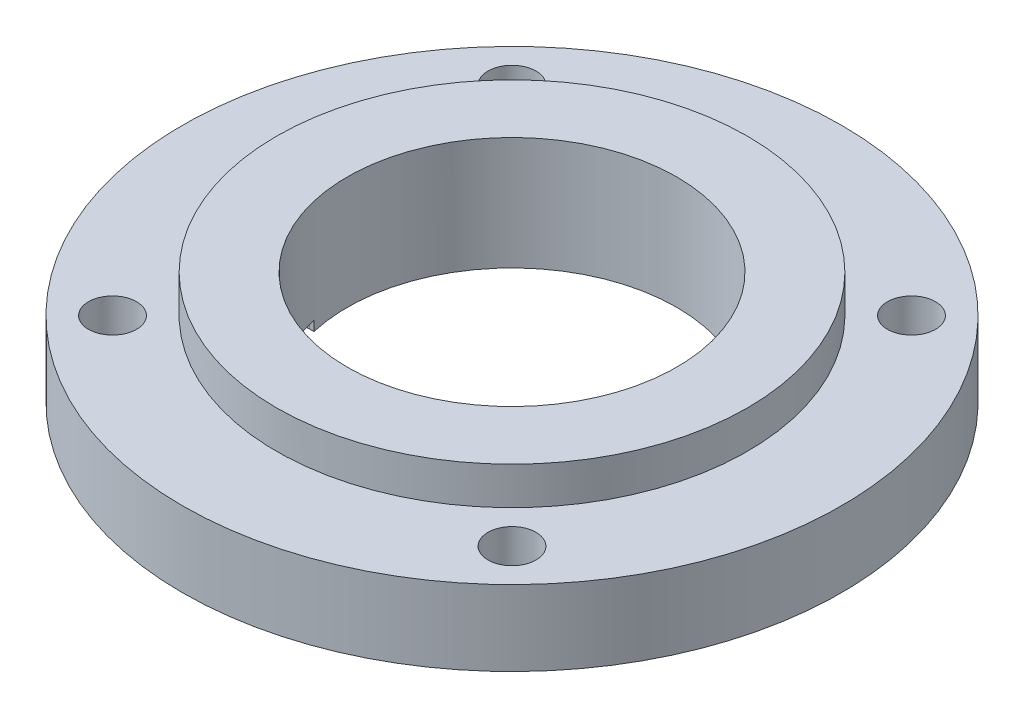
SolidWorks part; units mm, degrees
ref_plane "Front Plane" through (0, 0, 0) normal (0, 0, 1) x (1, 0, 0)
ref_plane "Top Plane" through (0, 0, 0) normal (0, 1, 0) x (1, 0, 0)
ref_plane "Right Plane" through (0, 0, 0) normal (1, 0, 0) x (0, 0, -1)
sketch "Sketch1" plane through (0, 0, 0) normal (0, 1, 0) x (1, 0, 0)
  circle A0 centre (0, 0) radius 25
  circle A1 centre (0, 0) radius 17.5
  dimension "D1" = 50
  dimension "D2" = 35
extrude "Boss-Extrude2" add sketch "Sketch1" along normal blind 12
sketch "Sketch4" plane through (0, 0, 0) normal (0, -1, 0) x (1, 0, 0)
  line L0 (0, 0) -> (0, 12.6931) construction
  line L1 (0, 0) -> (47.3741, 0) construction
  line L2 (0, 0) -> (-39.6318, 39.6318) construction
  circle A0 centre (0, 0) radius 35
  circle A1 centre (0, 0) radius 25
  circle A2 centre (-21.2132, 21.2132) radius 2.55
  circle A3 centre (21.2132, 21.2132) radius 2.55
  circle A4 centre (21.2132, -21.2132) radius 2.55
  circle A5 centre (-21.2132, -21.2132) radius 2.55
  point P19 (0, 0)
  point P22 (0, 0)
  dimension "D1" = 70
  dimension "D2" = 5.1
  dimension "D3" = 30
  dimension "D4" = 4
extrude "Boss-Extrude3" add sketch "Sketch4" against normal blind 8
sketch "Sketch2" plane through (0, 0, 0) normal (0, 1, 0) x (1, 0, 0)
  line L0 (-7.8, -11.4396) -> (7.8, -11.4396)
  line L1 (0, 5.2614) -> (0, -30.8617) construction
  line L2 (-7.8, -11.4396) -> (-7.8, -25.54)
  line L3 (-17.5, -4) -> (17.5, -4)
  line L4 (0, -4) -> (0, -12) construction
  line L5 (0, -8) -> (17.5, -8) construction
  line L6 (17.5, -12) -> (-17.5, -12)
  line L7 (-7.8, -25.54) -> (7.8, -25.54)
  line L8 (7.8, -11.4396) -> (7.8, -25.54)
  line L9 (-7.8, -11.4396) -> (7.8, -25.54) construction
  line L10 (-7.8, -25.54) -> (7.8, -11.4396) construction
  arc A2 (17.5, -4) -> (17.5, -12) centre (17.5, -8) cw
  circle A3 centre (17.5, -8) radius 2
  circle A4 centre (-17.5, -8) radius 2
  arc A5 (-17.5, -4) -> (-17.5, -12) centre (-17.5, -8) ccw
  circle A6 centre (0, -8) radius 14.5
  point P3 (0, -18.4898)
  point P22 (0, -8)
  dimension "D5" = 4
  dimension "D9" = 29
  dimension "D4" = 8
  dimension "D6" = 35
  dimension "D1" = 0
  dimension "D7" = 15.6
  dimension "D8" = 0
  dimension "D2" = 8
  dimension "D3" = 25.54
extrude "Cut-Extrude2" cut sketch "Sketch2" along normal blind 1.05 contours L6 A6 L2 | L8 A6 L6 | A4 | A3
equation "\"Bearing outside diameter\"= 35mm"
equation "\"Base support outside diameter\"= 50mm"
equation "\"D1@Sketch1\"=\"Base support outside diameter\""
equation "\"D2@Sketch1\"=\"Bearing outside diameter\""
equation "\"Bearing height\"= 9mm"
equation "\"D1@Boss-Extrude2\"=\"Bearing height\"+\"stepper motor shaft shoulder\"+\"stepper motor mount thickness\"+0.5mm"
equation "\"stepper motor hole distance\"= 35mm"
equation "\"stepper motor shaft center offset\"= 8mm"
equation "\"stepper motor shaft shoulder\"= 1.5mm"
equation "\"stepper motor mount thickness\"= 1mm"
equation "\"Mount section diameter\"= 70mm"
equation "\"mount section thickness\"= 8mm"
equation "\"D1@Boss-Extrude3\"=\"mount section thickness\""
equation "\"D1@Sketch4\"=\"Mount section diameter\""
equation "\"D9@Sketch2\"=29mm"
equation "\"D2@Sketch4\"=5.1mm"
equation "\"D3@Sketch4\"=\"Mount section diameter\"/2-5mm"
